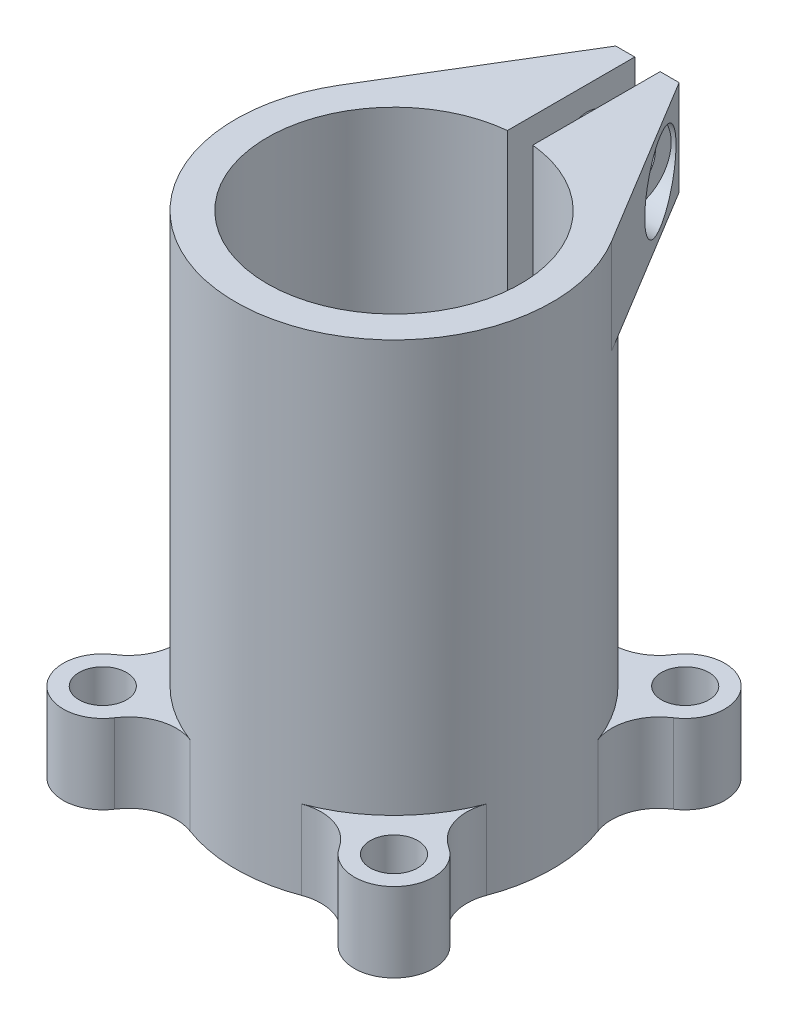
SolidWorks part; units mm, degrees
material "6061 合金"
ref_plane "前视基准面" through (0, 0, 0) normal (0, 0, 1) x (1, 0, 0)
ref_plane "上视基准面" through (0, 0, 0) normal (0, 1, 0) x (1, 0, 0)
ref_plane "右视基准面" through (0, 0, 0) normal (1, 0, 0) x (0, 0, -1)
sketch "草图1" plane through (0, 0, 0) normal (0, 1, 0) x (1, 0, 0)
  line L0 (0, 0) -> (13, 0) construction
  line L1 (0, 0) -> (9.1924, 9.1924) construction
  arc A0 (3.5143, 9.3621) -> (-3.5143, 9.3621) centre (0, 0) ccw
  circle A1 centre (0, 0) radius 13 construction
  circle A2 centre (9.1924, 9.1924) radius 1.5
  arc A3 (10.5462, 7.0907) -> (7.0907, 10.5462) centre (9.1924, 9.1924) ccw
  arc A4 (3.5143, 9.3621) -> (7.2369, 10.7994) centre (4.5686, 12.1708) ccw
  arc A5 (9.3621, 3.5143) -> (10.7994, 7.2369) centre (12.1708, 4.5686) cw
  arc A6 (7.0907, -10.5462) -> (10.5462, -7.0907) centre (9.1924, -9.1924) ccw
  circle A7 centre (9.1924, -9.1924) radius 1.5
  arc A8 (3.5143, -9.3621) -> (7.2369, -10.7994) centre (4.5686, -12.1708) cw
  arc A9 (9.3621, -3.5143) -> (10.7994, -7.2369) centre (12.1708, -4.5686) ccw
  arc A10 (-10.5462, -7.0907) -> (-7.0907, -10.5462) centre (-9.1924, -9.1924) ccw
  circle A11 centre (-9.1924, -9.1924) radius 1.5
  arc A12 (-9.3621, -3.5143) -> (-10.7994, -7.2369) centre (-12.1708, -4.5686) cw
  arc A13 (-3.5143, -9.3621) -> (-7.2369, -10.7994) centre (-4.5686, -12.1708) ccw
  arc A14 (-7.0907, 10.5462) -> (-10.5462, 7.0907) centre (-9.1924, 9.1924) ccw
  circle A15 centre (-9.1924, 9.1924) radius 1.5
  arc A16 (-3.5143, 9.3621) -> (-7.2369, 10.7994) centre (-4.5686, 12.1708) cw
  arc A17 (-9.3621, 3.5143) -> (-10.7994, 7.2369) centre (-12.1708, 4.5686) ccw
  arc A18 (-9.3621, 3.5143) -> (-9.3621, -3.5143) centre (0, 0) ccw
  arc A19 (-3.5143, -9.3621) -> (3.5143, -9.3621) centre (0, 0) ccw
  arc A20 (9.3621, -3.5143) -> (9.3621, 3.5143) centre (0, 0) ccw
  point P47 (0, 0)
  dimension "D1" = 20
  dimension "D2" = 26
  dimension "D4" = 3
  dimension "D5" = 5
  dimension "D6" = 6
  dimension "D3" = 45
  dimension "D7" = 4
extrude "凸台-拉伸1" add sketch "草图1" along normal blind 5 contours A9 A20 A5 A3 A4 A0 A16 A14 A17 A18 A12 A10 A13 A19 A8 A6 A2 A7 A11 A15
sketch "草图2" plane through (0, 5, 0) normal (0, 1, 0) x (1, 0, 0)
  circle A0 centre (0, 0) radius 10
  dimension "D1" = 20
extrude "凸台-拉伸2" add sketch "草图2" along normal blind 26
sketch "草图3" plane through (0, 31, 0) normal (0, 1, 0) x (1, 0, 0)
  circle A0 centre (0, 0) radius 8
  dimension "D1" = 16
extrude "切除-拉伸1" cut sketch "草图3" against normal through all
sketch "草图4" plane through (0, 31, 0) normal (0, 1, 0) x (1, 0, 0)
  line L0 (0, 0) -> (0, 13.8179) construction
  line L1 (-8.5533, 5.1808) -> (-2, 16)
  line L2 (-2, 16) -> (2, 16)
  line L3 (8.5533, 5.1808) -> (2, 16)
  circle A0 centre (0, 0) radius 10 construction
  circle A1 centre (0, 0) radius 10
  arc A2 (8.5533, 5.1808) -> (-8.5533, 5.1808) centre (0, 0) ccw
  point P14 (0, 16)
  dimension "D2" = 16
  dimension "D3" = 2
  dimension "D1" = 0
extrude "凸台-拉伸3" add sketch "草图4" against normal blind 6
sketch "草图5" plane through (0, 31, 0) normal (0, 1, 0) x (1, 0, 0)
  line L0 (0, 0) -> (0, 16) construction
  line L1 (2, 16) -> (-2, 16) construction
  line L2 (-0.8, 16) -> (0.8, 16)
  line L3 (0.8, 16) -> (0.8, 0)
  line L4 (0.8, 0) -> (-0.8, 0)
  line L5 (-0.8, 16) -> (-0.8, 0)
  dimension "D1" = 0.8
extrude "切除-拉伸2" cut sketch "草图5" against normal blind 25
sketch "草图6" plane through (0, 0, 0) normal (1, 0, 0) x (0, 0, -1)
  line L0 (16, 28) -> (5.1808, 28) construction
  line L1 (16, 25) -> (16, 31) construction
  line L2 (5.1808, 25) -> (5.1808, 31) construction
  circle A0 centre (13, 28) radius 1.5
  dimension "D1" = 3
  dimension "D2" = 3
extrude "切除-拉伸3" cut sketch "草图6" against normal through all both and the other way through all
ref_plane "基准面1" through (10, 0, 0) normal (1, 0, 0) x (0, 0, -1)
sketch "草图7" plane through (10, 0, 0) normal (1, 0, 0) x (0, 0, -1)
  circle A0 centre (13, 28) radius 2.5
  dimension "D1" = 5
extrude "切除-拉伸4" cut sketch "草图7" against normal blind 8
